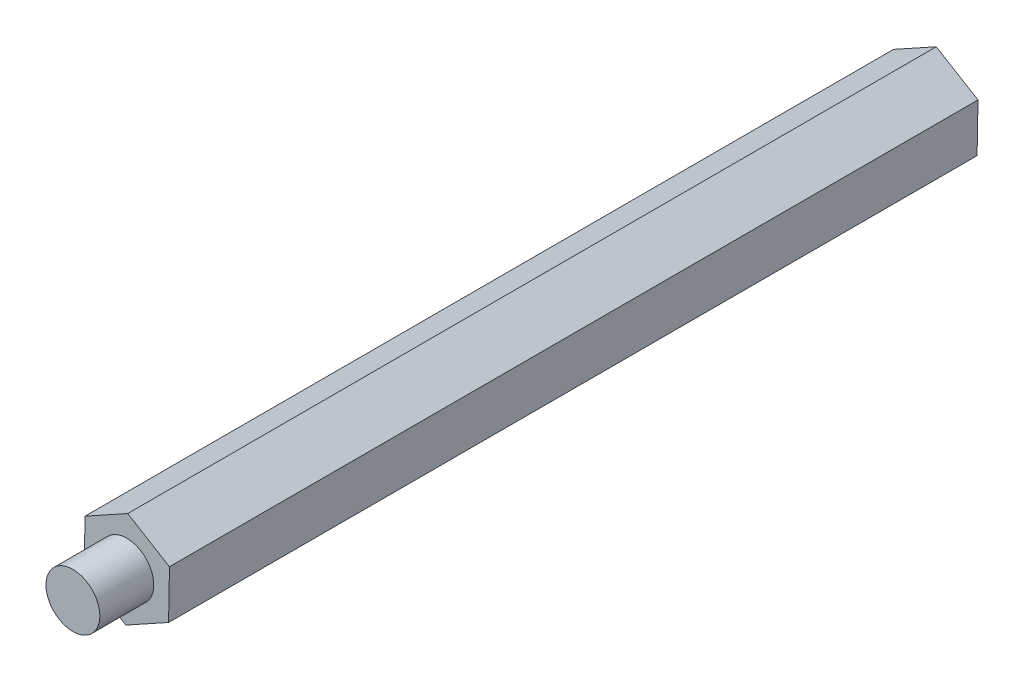
SolidWorks part; units mm, degrees
ref_plane "前视基准面" through (0, 0, 0) normal (0, 0, 1) x (1, 0, 0)
ref_plane "上视基准面" through (0, 0, 0) normal (0, 1, 0) x (1, 0, 0)
ref_plane "右视基准面" through (0, 0, 0) normal (1, 0, 0) x (0, 0, -1)
other "Configuration Table"
sketch "草图1" plane through (0, 0, 0) normal (0, 0, 1) x (1, 0, 0)
  line L1 (-2.3242, 1.4005) -> (-2.375, -1.3126)
  line L2 (-2.375, -1.3126) -> (-0.0508, -2.7131)
  line L3 (-0.0508, -2.7131) -> (2.3242, -1.4005)
  line L4 (2.3242, -1.4005) -> (2.375, 1.3126)
  line L5 (2.375, 1.3126) -> (0.0508, 2.7131)
  line L6 (0.0508, 2.7131) -> (-2.3242, 1.4005)
  circle A0 centre (0, 0) radius 2.35 construction
  point P1 (-1.1367, 2.0568)
  point P10 (1.1367, -2.0568)
  dimension "D1" = 4.7
extrude "凸台-拉伸1" add sketch "草图1" along normal blind 45
sketch "草图2" plane through (0, 0, 45) normal (0, 0, 1) x (1, 0, 0)
  circle A0 centre (0, 0) radius 1.5
  dimension "D1" = 3
extrude "凸台-拉伸2" add sketch "草图2" along normal blind 3
sketch "草图3" plane through (0, 0, 0) normal (0, 0, -1) x (-1, 0, 0)
  circle A0 centre (0, 0) radius 1.5
  dimension "D1" = 3
extrude "切除-拉伸1" cut sketch "草图3" against normal blind 3
